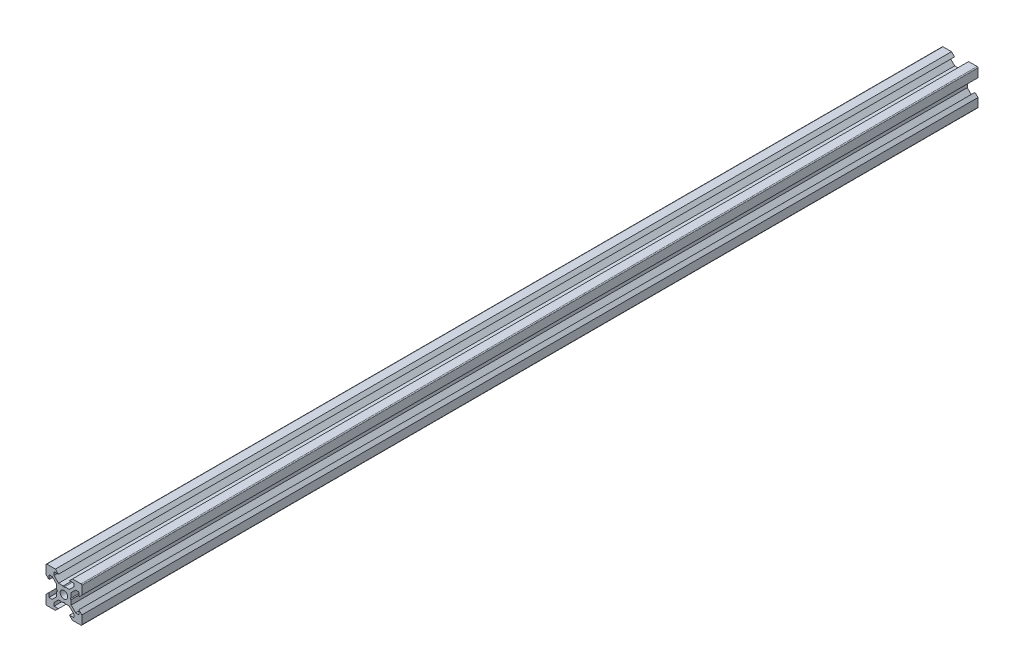
SolidWorks part; units mm, degrees
ref_plane "Front Plane" through (0, 0, 0) normal (0, 0, 1) x (1, 0, 0)
ref_plane "Top Plane" through (0, 0, 0) normal (0, 1, 0) x (1, 0, 0)
ref_plane "Right Plane" through (0, 0, 0) normal (1, 0, 0) x (0, 0, -1)
sketch "Sketch1" plane through (0, 0, 0) normal (0, 0, 1) x (1, 0, 0)
  line L0 (0, 11.7715) -> (0, -11.0375) construction
  line L1 (-10, 10) -> (10, 10) construction
  line L2 (-10, 10) -> (-10, -10) construction
  line L3 (-10, -10) -> (10, -10) construction
  line L4 (10, 10) -> (10, -10) construction
  line L5 (-10, 10) -> (10, -10) construction
  line L6 (-10, -10) -> (10, 10) construction
  line L7 (-5.5, 5.5) -> (5.5, 5.5) construction
  line L8 (-5.5, 5.5) -> (-5.5, -5.5) construction
  line L9 (-5.5, -5.5) -> (5.5, -5.5) construction
  line L10 (5.5, 5.5) -> (5.5, -5.5) construction
  line L11 (-5.5, 5.5) -> (5.5, -5.5) construction
  line L12 (-5.5, -5.5) -> (5.5, 5.5) construction
  line L13 (-10, 10) -> (-4.775, 10)
  line L14 (-4.775, 10) -> (-3.1, 8.325)
  line L15 (-3.1, 8.325) -> (-5.5, 8.325)
  line L16 (-5.5, 8.325) -> (-5.5, 6.525)
  line L17 (-5.5, 6.525) -> (-3, 4.025)
  line L18 (-3, 4.025) -> (3, 4.025)
  line L19 (-2.8044, 0) -> (3.0922, 0) construction
  line L20 (5.5, 6.525) -> (3, 4.025)
  line L21 (5.5, 8.325) -> (5.5, 6.525)
  line L22 (3.1, 8.325) -> (5.5, 8.325)
  line L23 (4.775, 10) -> (3.1, 8.325)
  line L24 (10, 10) -> (4.775, 10)
  line L25 (10, -10) -> (4.775, -10)
  line L26 (4.775, -10) -> (3.1, -8.325)
  line L27 (3.1, -8.325) -> (5.5, -8.325)
  line L28 (5.5, -8.325) -> (5.5, -6.525)
  line L29 (5.5, -6.525) -> (3, -4.025)
  line L30 (-3.1, -8.325) -> (-5.5, -8.325)
  line L31 (-3, -4.025) -> (3, -4.025)
  line L32 (-5.5, -6.525) -> (-3, -4.025)
  line L33 (-5.5, -8.325) -> (-5.5, -6.525)
  line L34 (-4.775, -10) -> (-3.1, -8.325)
  line L35 (-10, -10) -> (-4.775, -10)
  line L36 (-4.025, 3) -> (-4.025, -3)
  line L37 (-6.525, 5.5) -> (-4.025, 3)
  line L38 (-8.325, 5.5) -> (-6.525, 5.5)
  line L39 (-8.325, 3.1) -> (-8.325, 5.5)
  line L40 (-10, 4.775) -> (-8.325, 3.1)
  line L41 (-10, 10) -> (-10, 4.775)
  line L42 (-10, -10) -> (-10, -4.775)
  line L43 (-10, -4.775) -> (-8.325, -3.1)
  line L44 (-8.325, -3.1) -> (-8.325, -5.5)
  line L45 (-8.325, -5.5) -> (-6.525, -5.5)
  line L46 (-6.525, -5.5) -> (-4.025, -3)
  line L47 (10, -10) -> (10, -4.775)
  line L48 (10, -4.775) -> (8.325, -3.1)
  line L49 (8.325, -3.1) -> (8.325, -5.5)
  line L50 (8.325, -5.5) -> (6.525, -5.5)
  line L51 (6.525, -5.5) -> (4.025, -3)
  line L52 (4.025, 3) -> (4.025, -3)
  line L53 (6.525, 5.5) -> (4.025, 3)
  line L54 (8.325, 5.5) -> (6.525, 5.5)
  line L55 (8.325, 3.1) -> (8.325, 5.5)
  line L56 (10, 4.775) -> (8.325, 3.1)
  line L57 (10, 10) -> (10, 4.775)
  circle A0 centre (0, 0) radius 2.1
  point P0 (0, 0)
  point P6 (0, 0)
  point P23 (0, 4.025)
  dimension "D3" = 4.2
  dimension "D1" = 20
  dimension "D2" = 20
  dimension "D4" = 45
  dimension "D5" = 45
  dimension "D6" = 9.55
  dimension "D7" = 6.2
  dimension "D8" = 11
  dimension "D9" = 1.675
  dimension "D10" = 4.3
  dimension "D11" = 9.55
  dimension "D12" = 6.2
  dimension "D13" = 1.675
  dimension "D14" = 4.3
  dimension "D15" = 1.8
  dimension "D16" = 1.8
  dimension "D17" = 45
extrude "Boss-Extrude1" add sketch "Sketch1" along normal blind 500
fillet "Fillet1" radius 0.5 4 edges at (-10, -10, 250) (10, -10, 250) (10, 10, 250) (-10, 10, 250)
sketch "Sketch2" plane through (0, 0, 500) normal (0, 0, 1) x (1, 0, 0)
  line L0 (-0.8203, 0) -> (1.3478, 0) construction
  line L1 (0, 1.2196) -> (0, -1.1398) construction
  line L44 (-10, -4.775) -> (-10, -9.5)
  line L45 (-9.5, -10) -> (-4.775, -10)
  line L46 (-4.775, -10) -> (-3.1, -8.325)
  line L47 (-3.1, -8.325) -> (-5.5, -8.325)
  line L48 (-5.5, -8.325) -> (-5.5, -6.525)
  line L49 (-5.5, -6.525) -> (-3, -4.025)
  line L50 (-3, -4.025) -> (3, -4.025)
  line L51 (3, -4.025) -> (5.5, -6.525)
  line L52 (5.5, -6.525) -> (5.5, -8.325)
  line L53 (5.5, -8.325) -> (3.1, -8.325)
  line L54 (3.1, -8.325) -> (4.775, -10)
  line L55 (4.775, -10) -> (9.5, -10)
  line L56 (10, -9.5) -> (10, -4.775)
  line L57 (10, -4.775) -> (8.325, -3.1)
  line L58 (8.325, -3.1) -> (8.325, -5.5)
  line L59 (8.325, -5.5) -> (6.525, -5.5)
  line L60 (6.525, -5.5) -> (4.025, -3)
  line L61 (4.025, -3) -> (4.025, 3)
  line L62 (4.025, 3) -> (6.525, 5.5)
  line L63 (6.525, 5.5) -> (8.325, 5.5)
  line L64 (8.325, 5.5) -> (8.325, 3.1)
  line L65 (8.325, 3.1) -> (10, 4.775)
  line L66 (10, 4.775) -> (10, 9.5)
  line L67 (9.5, 10) -> (4.775, 10)
  line L68 (4.775, 10) -> (3.1, 8.325)
  line L69 (3.1, 8.325) -> (5.5, 8.325)
  line L70 (5.5, 8.325) -> (5.5, 6.525)
  line L71 (5.5, 6.525) -> (3, 4.025)
  line L72 (3, 4.025) -> (-3, 4.025)
  line L73 (-3, 4.025) -> (-5.5, 6.525)
  line L74 (-5.5, 6.525) -> (-5.5, 8.325)
  line L75 (-5.5, 8.325) -> (-3.1, 8.325)
  line L76 (-3.1, 8.325) -> (-4.775, 10)
  line L77 (-4.775, 10) -> (-9.5, 10)
  line L78 (-10, 9.5) -> (-10, 4.775)
  line L79 (-10, 4.775) -> (-8.325, 3.1)
  line L80 (-8.325, 3.1) -> (-8.325, 5.5)
  line L81 (-8.325, 5.5) -> (-6.525, 5.5)
  line L82 (-6.525, 5.5) -> (-4.025, 3)
  line L83 (-4.025, 3) -> (-4.025, -3)
  line L84 (-4.025, -3) -> (-6.525, -5.5)
  line L85 (-6.525, -5.5) -> (-8.325, -5.5)
  line L86 (-8.325, -5.5) -> (-8.325, -3.1)
  line L87 (-8.325, -3.1) -> (-10, -4.775)
  line L88 (-10, -4.775) -> (-10, -9.5)
  line L89 (-9.5, -10) -> (-4.775, -10)
  line L90 (-4.775, -10) -> (-3.1, -8.325)
  line L91 (-3.1, -8.325) -> (-5.5, -8.325)
  line L92 (-5.5, -8.325) -> (-5.5, -6.525)
  line L93 (-5.5, -6.525) -> (-3, -4.025)
  line L94 (-3, -4.025) -> (3, -4.025)
  line L95 (3, -4.025) -> (5.5, -6.525)
  line L96 (5.5, -6.525) -> (5.5, -8.325)
  line L97 (5.5, -8.325) -> (3.1, -8.325)
  line L98 (3.1, -8.325) -> (4.775, -10)
  line L99 (4.775, -10) -> (9.5, -10)
  line L100 (10, -9.5) -> (10, -4.775)
  line L101 (10, -4.775) -> (8.325, -3.1)
  line L102 (8.325, -3.1) -> (8.325, -5.5)
  line L103 (8.325, -5.5) -> (6.525, -5.5)
  line L104 (6.525, -5.5) -> (4.025, -3)
  line L105 (4.025, -3) -> (4.025, 3)
  line L106 (4.025, 3) -> (6.525, 5.5)
  line L107 (6.525, 5.5) -> (8.325, 5.5)
  line L108 (8.325, 5.5) -> (8.325, 3.1)
  line L109 (8.325, 3.1) -> (10, 4.775)
  line L110 (10, 4.775) -> (10, 9.5)
  line L111 (9.5, 10) -> (4.775, 10)
  line L112 (4.775, 10) -> (3.1, 8.325)
  line L113 (3.1, 8.325) -> (5.5, 8.325)
  line L114 (5.5, 8.325) -> (5.5, 6.525)
  line L115 (5.5, 6.525) -> (3, 4.025)
  line L116 (3, 4.025) -> (-3, 4.025)
  line L117 (-3, 4.025) -> (-5.5, 6.525)
  line L118 (-5.5, 6.525) -> (-5.5, 8.325)
  line L119 (-5.5, 8.325) -> (-3.1, 8.325)
  line L120 (-3.1, 8.325) -> (-4.775, 10)
  line L121 (-4.775, 10) -> (-9.5, 10)
  line L122 (-10, 9.5) -> (-10, 4.775)
  line L123 (-10, 4.775) -> (-8.325, 3.1)
  line L124 (-8.325, 3.1) -> (-8.325, 5.5)
  line L125 (-8.325, 5.5) -> (-6.525, 5.5)
  line L126 (-6.525, 5.5) -> (-4.025, 3)
  line L127 (-4.025, 3) -> (-4.025, -3)
  line L128 (-4.025, -3) -> (-6.525, -5.5)
  line L129 (-6.525, -5.5) -> (-8.325, -5.5)
  line L130 (-8.325, -5.5) -> (-8.325, -3.1)
  line L131 (-8.325, -3.1) -> (-10, -4.775)
  circle A0 centre (-4.025, 0) radius 0.4
  circle A1 centre (4.025, 0) radius 0.4
  circle A2 centre (0, 4.025) radius 0.4
  circle A3 centre (0, -4.025) radius 0.4
  arc A4 (-10, -9.5) -> (-9.5, -10) centre (-9.5, -9.5) ccw
  arc A5 (9.5, -10) -> (10, -9.5) centre (9.5, -9.5) ccw
  arc A6 (10, 9.5) -> (9.5, 10) centre (9.5, 9.5) ccw
  arc A7 (-9.5, 10) -> (-10, 9.5) centre (-9.5, 9.5) ccw
  arc A8 (-10, -9.5) -> (-9.5, -10) centre (-9.5, -9.5) ccw
  arc A9 (9.5, -10) -> (10, -9.5) centre (9.5, -9.5) ccw
  arc A10 (10, 9.5) -> (9.5, 10) centre (9.5, 9.5) ccw
  arc A11 (-9.5, 10) -> (-10, 9.5) centre (-9.5, 9.5) ccw
  dimension "D2" = 0.8
  dimension "D3" = 0.8
  dimension "D1" = 0
extrude "Cut-Extrude1" cut sketch "Sketch2" against normal through all contours L127 A0 | L116 A2 | A1 L105 | A3 L94
